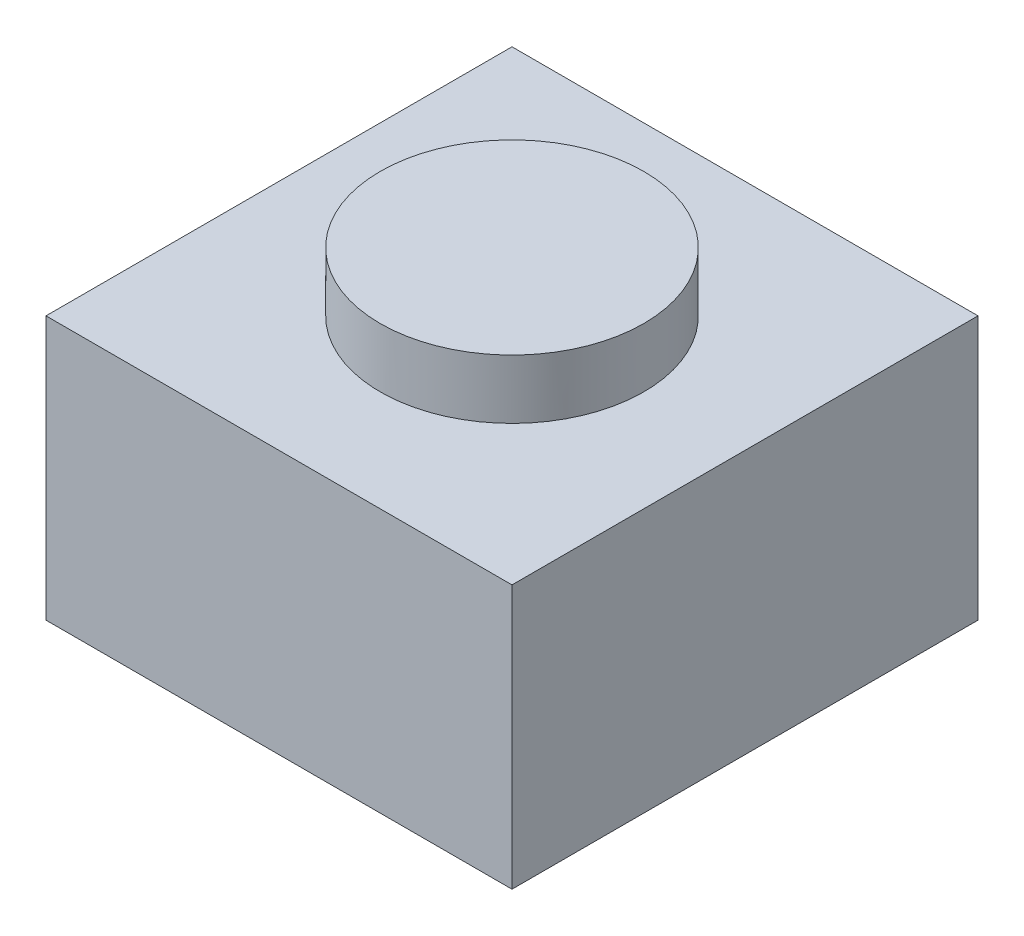
SolidWorks part; units mm, degrees
ref_plane "Front Plane" through (0, 0, 0) normal (0, 0, 1) x (1, 0, 0)
ref_plane "Top Plane" through (0, 0, 0) normal (0, 1, 0) x (1, 0, 0)
ref_plane "Right Plane" through (0, 0, 0) normal (1, 0, 0) x (0, 0, -1)
sketch "Sketch1" plane through (0, 0, 0) normal (0, 1, 0) x (1, 0, 0)
  line L1 (0, 0) -> (6.1976, 0)
  line L2 (0, 0) -> (0, 6.1976)
  line L3 (0, 6.1976) -> (6.1976, 6.1976)
  line L4 (6.1976, 0) -> (6.1976, 6.1976)
  dimension "D1" = 6.1976
  dimension "D2" = 6.1976
extrude "Boss-Extrude1" add sketch "Sketch1" along normal blind 3.5052
sketch "Sketch2" plane through (0, 3.5052, 0) normal (0, 1, 0) x (1, 0, 0)
  circle A0 centre (3.0988, 3.0988) radius 1.7526
  dimension "D1" = 3.5052
extrude "Boss-Extrude2" add sketch "Sketch2" along normal blind 0.7874
